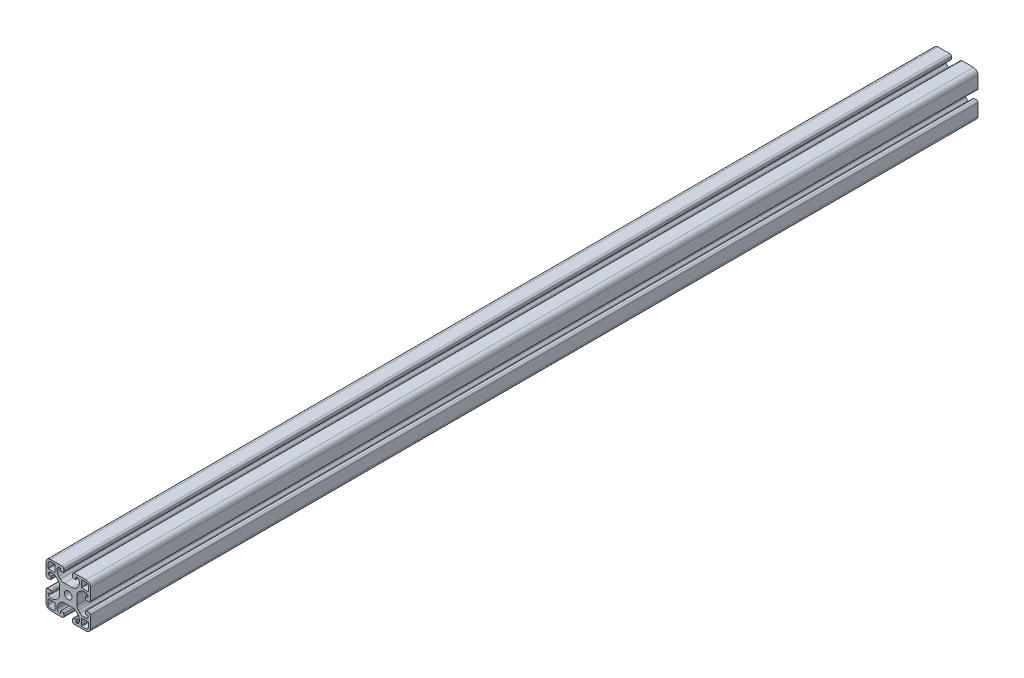
SolidWorks part; units mm, degrees
ref_plane "Plan de face" through (0, 0, 0) normal (0, 0, 1) x (1, 0, 0)
ref_plane "Plan de dessus" through (0, 0, 0) normal (0, 1, 0) x (1, 0, 0)
ref_plane "Plan de droite" through (0, 0, 0) normal (1, 0, 0) x (0, 0, -1)
ref_plane "Plan1" through (0, 0, -30) normal (0, 0, -1) x (-1, 0, 0)
sketch "Esquisse1" plane through (0, 0, -30) normal (0, 0, -1) x (-1, 0, 0)
  line L0 (-4.5, 15) -> (-4.5, 13.5)
  line L1 (-4, 13) -> (-2.5, 13)
  line L2 (-4.5, 10) -> (-5.8076, 10)
  line L3 (-9.3431, 11.4645) -> (-10.7855, 12.9069)
  line L4 (-12.25, 16.4424) -> (-12.25, 23.5576)
  line L5 (-10.7855, 27.0931) -> (-9.3431, 28.5355)
  line L6 (-5.8076, 30) -> (-4.5, 30)
  line L7 (-2.5, 27) -> (-4, 27)
  line L8 (-4.5, 26.5) -> (-4.5, 25)
  line L9 (-3.5, 24) -> (-1.5, 24)
  line L10 (0, 25.5) -> (0, 36)
  line L11 (-4, 40) -> (-14.5, 40)
  line L12 (-16, 38.5) -> (-16, 36.5)
  line L13 (-15, 35.5) -> (-13.5, 35.5)
  line L14 (-13, 36) -> (-13, 37.5)
  line L15 (-10, 35.5) -> (-10, 34.1924)
  line L16 (-11.4645, 30.6569) -> (-12.9069, 29.2145)
  line L17 (-16.4424, 27.75) -> (-23.5576, 27.75)
  line L18 (-27.0931, 29.2145) -> (-28.5355, 30.6569)
  line L19 (-30, 34.1924) -> (-30, 35.5)
  line L20 (-27, 37.5) -> (-27, 36)
  line L21 (-26.5, 35.5) -> (-25, 35.5)
  line L22 (-24, 36.5) -> (-24, 38.5)
  line L23 (-25.5, 40) -> (-36, 40)
  line L24 (-40, 36) -> (-40, 25.5)
  line L25 (-38.5, 24) -> (-36.5, 24)
  line L26 (-35.5, 25) -> (-35.5, 26.5)
  line L27 (-36, 27) -> (-37.5, 27)
  line L28 (-35.5, 30) -> (-34.1924, 30)
  line L29 (-30.6569, 28.5355) -> (-29.2145, 27.0931)
  line L30 (-27.75, 23.5576) -> (-27.75, 16.4424)
  line L31 (-29.2145, 12.9069) -> (-30.6569, 11.4645)
  line L32 (-34.1924, 10) -> (-35.5, 10)
  line L33 (-37.5, 13) -> (-36, 13)
  line L34 (-35.5, 13.5) -> (-35.5, 15)
  line L35 (-36.5, 16) -> (-38.5, 16)
  line L36 (-40, 14.5) -> (-40, 4)
  line L37 (-36, 0) -> (-25.5, 0)
  line L38 (-24, 1.5) -> (-24, 3.5)
  line L39 (-25, 4.5) -> (-26.5, 4.5)
  line L40 (-27, 4) -> (-27, 2.5)
  line L41 (-30, 4.5) -> (-30, 5.8076)
  line L42 (-28.5355, 9.3431) -> (-27.0931, 10.7855)
  line L43 (-23.5576, 12.25) -> (-16.4424, 12.25)
  line L44 (-12.9069, 10.7855) -> (-11.4645, 9.3431)
  line L45 (-10, 5.8076) -> (-10, 4.5)
  line L46 (-13, 2.5) -> (-13, 4)
  line L47 (-13.5, 4.5) -> (-15, 4.5)
  line L48 (-16, 3.5) -> (-16, 1.5)
  line L49 (-14.5, 0) -> (-4, 0)
  line L50 (0, 4) -> (0, 14.5)
  line L51 (-1.5, 16) -> (-3.5, 16)
  line L52 (-4, 1.8) -> (-7.7, 1.8)
  line L53 (-8.2, 2.3) -> (-8.2, 7.7)
  line L54 (-7.7, 8.2) -> (-2.3, 8.2)
  line L55 (-1.8, 7.7) -> (-1.8, 4)
  line L56 (-38.2, 4) -> (-38.2, 7.7)
  line L57 (-37.7, 8.2) -> (-32.3, 8.2)
  line L58 (-31.8, 7.7) -> (-31.8, 2.3)
  line L59 (-32.3, 1.8) -> (-36, 1.8)
  line L60 (-36, 38.2) -> (-32.3, 38.2)
  line L61 (-31.8, 37.7) -> (-31.8, 32.3)
  line L62 (-32.3, 31.8) -> (-37.7, 31.8)
  line L63 (-38.2, 32.3) -> (-38.2, 36)
  line L64 (-1.8, 36) -> (-1.8, 32.3)
  line L65 (-2.3, 31.8) -> (-7.7, 31.8)
  line L66 (-8.2, 32.3) -> (-8.2, 37.7)
  line L67 (-7.7, 38.2) -> (-4, 38.2)
  arc A0 (-4.5, 13.5) -> (-4, 13) centre (-4, 13.5) ccw
  arc A1 (-2.5, 13) -> (-2, 12.5) centre (-2.5, 12.5) cw
  arc A2 (-2, 12.5) -> (-4.5, 10) centre (-4.5, 12.5) cw
  arc A3 (-5.8076, 10) -> (-9.3431, 11.4645) centre (-5.8076, 15) cw
  arc A4 (-10.7855, 12.9069) -> (-12.25, 16.4424) centre (-7.25, 16.4424) cw
  arc A5 (-12.25, 23.5576) -> (-10.7855, 27.0931) centre (-7.25, 23.5576) cw
  arc A6 (-9.3431, 28.5355) -> (-5.8076, 30) centre (-5.8076, 25) cw
  arc A7 (-4.5, 30) -> (-2, 27.5) centre (-4.5, 27.5) cw
  arc A8 (-2, 27.5) -> (-2.5, 27) centre (-2.5, 27.5) cw
  arc A9 (-4, 27) -> (-4.5, 26.5) centre (-4, 26.5) ccw
  arc A10 (-4.5, 25) -> (-3.5, 24) centre (-3.5, 25) ccw
  arc A11 (-1.5, 24) -> (0, 25.5) centre (-1.5, 25.5) ccw
  arc A12 (0, 36) -> (-4, 40) centre (-4, 36) ccw
  arc A13 (-14.5, 40) -> (-16, 38.5) centre (-14.5, 38.5) ccw
  arc A14 (-16, 36.5) -> (-15, 35.5) centre (-15, 36.5) ccw
  arc A15 (-13.5, 35.5) -> (-13, 36) centre (-13.5, 36) ccw
  arc A16 (-13, 37.5) -> (-12.5, 38) centre (-12.5, 37.5) cw
  arc A17 (-12.5, 38) -> (-10, 35.5) centre (-12.5, 35.5) cw
  arc A18 (-10, 34.1924) -> (-11.4645, 30.6569) centre (-15, 34.1924) cw
  arc A19 (-12.9069, 29.2145) -> (-16.4424, 27.75) centre (-16.4424, 32.75) cw
  arc A20 (-23.5576, 27.75) -> (-27.0931, 29.2145) centre (-23.5576, 32.75) cw
  arc A21 (-28.5355, 30.6569) -> (-30, 34.1924) centre (-25, 34.1924) cw
  arc A22 (-30, 35.5) -> (-27.5, 38) centre (-27.5, 35.5) cw
  arc A23 (-27.5, 38) -> (-27, 37.5) centre (-27.5, 37.5) cw
  arc A24 (-27, 36) -> (-26.5, 35.5) centre (-26.5, 36) ccw
  arc A25 (-25, 35.5) -> (-24, 36.5) centre (-25, 36.5) ccw
  arc A26 (-24, 38.5) -> (-25.5, 40) centre (-25.5, 38.5) ccw
  arc A27 (-36, 40) -> (-40, 36) centre (-36, 36) ccw
  arc A28 (-40, 25.5) -> (-38.5, 24) centre (-38.5, 25.5) ccw
  arc A29 (-36.5, 24) -> (-35.5, 25) centre (-36.5, 25) ccw
  arc A30 (-35.5, 26.5) -> (-36, 27) centre (-36, 26.5) ccw
  arc A31 (-37.5, 27) -> (-38, 27.5) centre (-37.5, 27.5) cw
  arc A32 (-38, 27.5) -> (-35.5, 30) centre (-35.5, 27.5) cw
  arc A33 (-34.1924, 30) -> (-30.6569, 28.5355) centre (-34.1924, 25) cw
  arc A34 (-29.2145, 27.0931) -> (-27.75, 23.5576) centre (-32.75, 23.5576) cw
  arc A35 (-27.75, 16.4424) -> (-29.2145, 12.9069) centre (-32.75, 16.4424) cw
  arc A36 (-30.6569, 11.4645) -> (-34.1924, 10) centre (-34.1924, 15) cw
  arc A37 (-35.5, 10) -> (-38, 12.5) centre (-35.5, 12.5) cw
  arc A38 (-38, 12.5) -> (-37.5, 13) centre (-37.5, 12.5) cw
  arc A39 (-36, 13) -> (-35.5, 13.5) centre (-36, 13.5) ccw
  arc A40 (-35.5, 15) -> (-36.5, 16) centre (-36.5, 15) ccw
  arc A41 (-38.5, 16) -> (-40, 14.5) centre (-38.5, 14.5) ccw
  arc A42 (-40, 4) -> (-36, 0) centre (-36, 4) ccw
  arc A43 (-25.5, 0) -> (-24, 1.5) centre (-25.5, 1.5) ccw
  arc A44 (-24, 3.5) -> (-25, 4.5) centre (-25, 3.5) ccw
  arc A45 (-26.5, 4.5) -> (-27, 4) centre (-26.5, 4) ccw
  arc A46 (-27, 2.5) -> (-27.5, 2) centre (-27.5, 2.5) cw
  arc A47 (-27.5, 2) -> (-30, 4.5) centre (-27.5, 4.5) cw
  arc A48 (-30, 5.8076) -> (-28.5355, 9.3431) centre (-25, 5.8076) cw
  arc A49 (-27.0931, 10.7855) -> (-23.5576, 12.25) centre (-23.5576, 7.25) cw
  arc A50 (-16.4424, 12.25) -> (-12.9069, 10.7855) centre (-16.4424, 7.25) cw
  arc A51 (-11.4645, 9.3431) -> (-10, 5.8076) centre (-15, 5.8076) cw
  arc A52 (-10, 4.5) -> (-12.5, 2) centre (-12.5, 4.5) cw
  arc A53 (-12.5, 2) -> (-13, 2.5) centre (-12.5, 2.5) cw
  arc A54 (-13, 4) -> (-13.5, 4.5) centre (-13.5, 4) ccw
  arc A55 (-15, 4.5) -> (-16, 3.5) centre (-15, 3.5) ccw
  arc A56 (-16, 1.5) -> (-14.5, 0) centre (-14.5, 1.5) ccw
  arc A57 (-4, 0) -> (0, 4) centre (-4, 4) ccw
  arc A58 (0, 14.5) -> (-1.5, 16) centre (-1.5, 14.5) ccw
  arc A59 (-3.5, 16) -> (-4.5, 15) centre (-3.5, 15) ccw
  circle A60 centre (-20, 20) radius 3.4
  arc A61 (-1.8, 4) -> (-4, 1.8) centre (-4, 4) cw
  arc A62 (-7.7, 1.8) -> (-8.2, 2.3) centre (-7.7, 2.3) cw
  arc A63 (-8.2, 7.7) -> (-7.7, 8.2) centre (-7.7, 7.7) cw
  arc A64 (-2.3, 8.2) -> (-1.8, 7.7) centre (-2.3, 7.7) cw
  arc A65 (-36, 1.8) -> (-38.2, 4) centre (-36, 4) cw
  arc A66 (-38.2, 7.7) -> (-37.7, 8.2) centre (-37.7, 7.7) cw
  arc A67 (-32.3, 8.2) -> (-31.8, 7.7) centre (-32.3, 7.7) cw
  arc A68 (-31.8, 2.3) -> (-32.3, 1.8) centre (-32.3, 2.3) cw
  arc A69 (-38.2, 36) -> (-36, 38.2) centre (-36, 36) cw
  arc A70 (-32.3, 38.2) -> (-31.8, 37.7) centre (-32.3, 37.7) cw
  arc A71 (-31.8, 32.3) -> (-32.3, 31.8) centre (-32.3, 32.3) cw
  arc A72 (-37.7, 31.8) -> (-38.2, 32.3) centre (-37.7, 32.3) cw
  arc A73 (-4, 38.2) -> (-1.8, 36) centre (-4, 36) cw
  arc A74 (-1.8, 32.3) -> (-2.3, 31.8) centre (-2.3, 32.3) cw
  arc A75 (-7.7, 31.8) -> (-8.2, 32.3) centre (-7.7, 32.3) cw
  arc A76 (-8.2, 37.7) -> (-7.7, 38.2) centre (-7.7, 37.7) cw
extrude "Boss.-Extru.1" add sketch "Esquisse1" against normal blind 800
